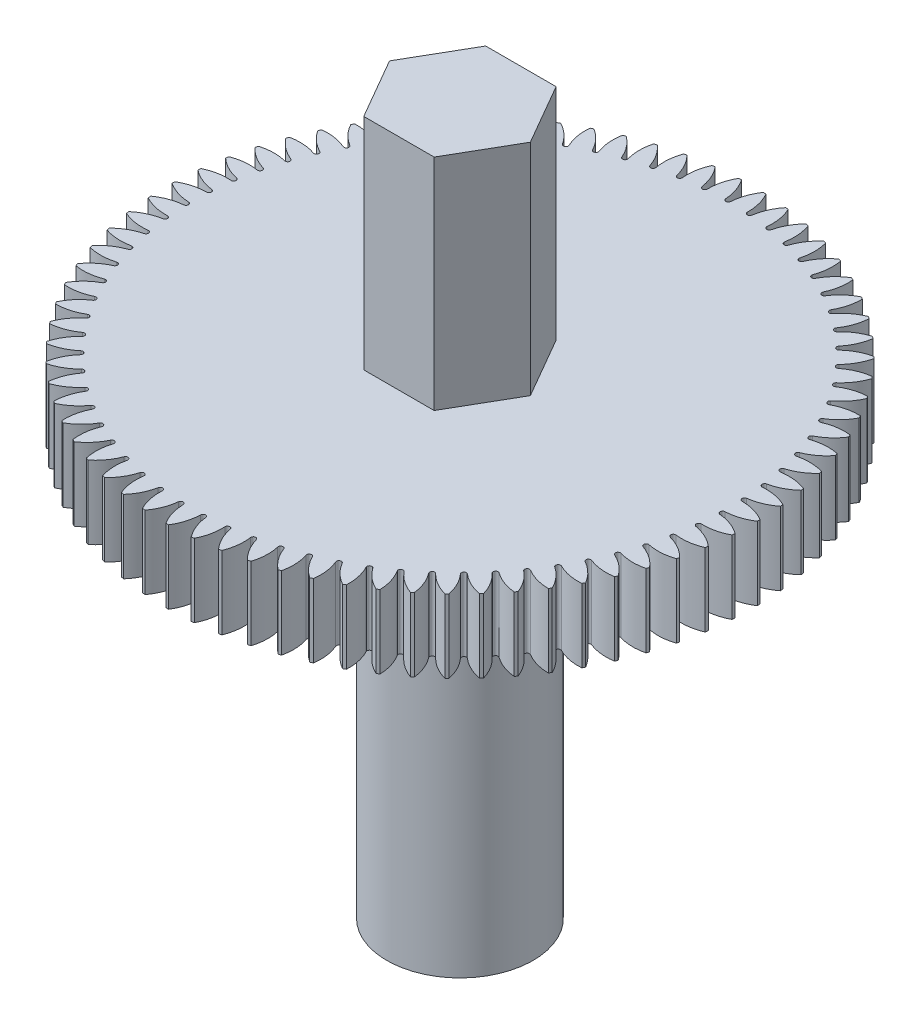
SolidWorks part; units mm, degrees
ref_plane "Front Plane" through (0, 0, 0) normal (0, 0, 1) x (1, 0, 0)
ref_plane "Top Plane" through (0, 0, 0) normal (0, 1, 0) x (1, 0, 0)
ref_plane "Right Plane" through (0, 0, 0) normal (1, 0, 0) x (0, 0, -1)
sketch "Sketch2" plane through (0, 0, 0) normal (0, 0, 1) x (1, 0, 0)
  line L1 (0, 0) -> (0, 29)
  line L2 (0, 29) -> (3, 29)
  line L3 (3, 29) -> (3, 20)
  line L4 (3, 20) -> (12, 20)
  line L5 (12, 20) -> (12, 17)
  line L6 (12, 17) -> (3, 17)
  line L7 (3, 17) -> (3, 0)
  line L8 (3, 0) -> (0, 0)
  dimension "D1" = 3
  dimension "D2" = 3
  dimension "29" = 29
  dimension "D3" = 9
  dimension "D4" = 3
  dimension "D5" = 17
revolve "Revolve1" add sketch "Sketch2" angle 360 about L1
sketch "Sketch3" plane through (0, 20, 0) normal (0, 1, 0) x (1, 0, 0)
  line L0 (0, 0) -> (0, 24) construction
  line L1 (-0.45, 12) -> (0.45, 12)
  circle A1 centre (0, 0) radius 3 construction
  arc A2 (0.45, 12) -> (0.0998, 10.9935) centre (2.0955, 10.8633) ccw
  arc A3 (0.0998, 10.9935) -> (-0.0998, 10.9935) centre (0, 11) cw
  arc A4 (-0.45, 12) -> (-0.0998, 10.9935) centre (-2.0955, 10.8633) cw
  point P8 (0, 12)
  dimension "D3" = 0.1
  dimension "D4" = 2
  dimension "D1" = 0.9
  dimension "D2" = 12
  dimension "D5" = 1
extrude "Cut-Extrude1" cut sketch "Sketch3" against normal blind 10
pattern_circular "CirPattern1" count 75 over 360 about axis through (0, 0, 0) along (0, 1, 0) of "Cut-Extrude1"
sketch "Sketch4" plane through (0, 29, 0) normal (0, 1, 0) x (1, 0, 0)
  line L1 (-1.4434, -2.5) -> (1.4434, -2.5)
  line L2 (1.4434, -2.5) -> (2.8868, 0)
  line L3 (2.8868, 0) -> (1.4434, 2.5)
  line L4 (1.4434, 2.5) -> (-1.4434, 2.5)
  line L5 (-1.4434, 2.5) -> (-2.8868, 0)
  line L6 (-2.8868, 0) -> (-1.4434, -2.5)
  circle A0 centre (0, 0) radius 2.5 construction
  circle A1 centre (0, 0) radius 3 construction
  circle A2 centre (0, 0) radius 3
  dimension "D1" = 5
extrude "Cut-Extrude2" cut sketch "Sketch4" against normal blind 9
